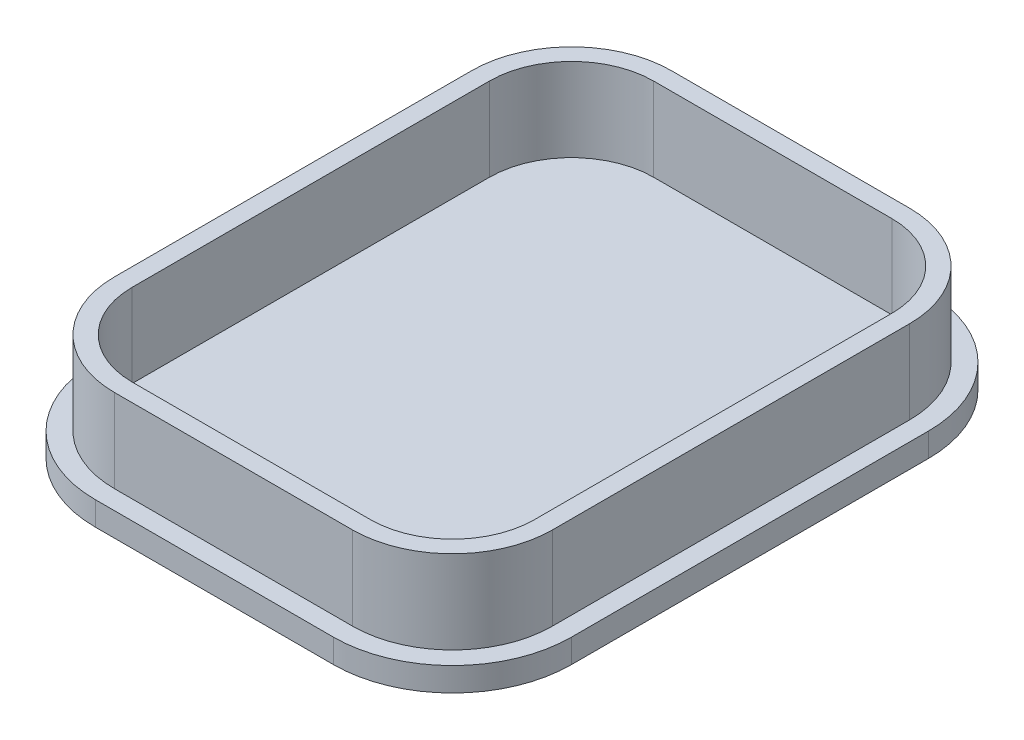
SolidWorks part; units mm, degrees
ref_plane "Plano frontal" through (0, 0, 0) normal (0, 0, 1) x (1, 0, 0)
ref_plane "Plano superior" through (0, 0, 0) normal (0, 1, 0) x (1, 0, 0)
ref_plane "Plano direito" through (0, 0, 0) normal (1, 0, 0) x (0, 0, -1)
sketch "Esboço1" plane through (0, 0, 0) normal (0, 1, 0) x (1, 0, 0)
  line L0 (-10.3488, -24.7614) -> (9.6512, -24.7614)
  line L1 (-20.3488, -14.7614) -> (-20.3488, 15.2386)
  line L2 (-10.3488, 25.2386) -> (9.6512, 25.2386)
  line L3 (19.6512, -14.7614) -> (19.6512, 15.2386)
  line L4 (-20.3488, -24.7614) -> (19.6512, 25.2386) construction
  line L5 (-20.3488, 25.2386) -> (19.6512, -24.7614) construction
  arc A0 (9.6512, 25.2386) -> (19.6512, 15.2386) centre (9.6512, 15.2386) cw
  arc A1 (9.6512, -24.7614) -> (19.6512, -14.7614) centre (9.6512, -14.7614) ccw
  arc A2 (-10.3488, -24.7614) -> (-20.3488, -14.7614) centre (-10.3488, -14.7614) cw
  arc A3 (-20.3488, 15.2386) -> (-10.3488, 25.2386) centre (-10.3488, 15.2386) cw
  point P0 (-0.3488, 0.2386)
  dimension "D1" = 10
extrude "Ressalto-extrusão1" add sketch "Esboço1" along normal blind 2
sketch "Esboço2" plane through (0, 2, 0) normal (0, 1, 0) x (1, 0, 0)
  line L4 (-17.2488, 15.2386) -> (-17.2488, -14.7614)
  line L5 (-10.3488, -21.6614) -> (9.6512, -21.6614)
  line L6 (16.5512, -14.7614) -> (16.5512, 15.2386)
  line L7 (9.6512, 22.1386) -> (-10.3488, 22.1386)
  line L8 (-18.7488, 15.2386) -> (-18.7488, -14.7614)
  line L9 (-10.3488, -23.1614) -> (9.6512, -23.1614)
  line L10 (18.0512, -14.7614) -> (18.0512, 15.2386)
  line L11 (9.6512, 23.6386) -> (-10.3488, 23.6386)
  line L12 (-18.7488, 15.2386) -> (-18.7488, -14.7614)
  line L13 (-10.3488, -23.1614) -> (9.6512, -23.1614)
  line L14 (18.0512, -14.7614) -> (18.0512, 15.2386)
  line L15 (9.6512, 23.6386) -> (-10.3488, 23.6386)
  arc A4 (-17.2488, -14.7614) -> (-10.3488, -21.6614) centre (-10.3488, -14.7614) ccw
  arc A5 (9.6512, -21.6614) -> (16.5512, -14.7614) centre (9.6512, -14.7614) ccw
  arc A6 (16.5512, 15.2386) -> (9.6512, 22.1386) centre (9.6512, 15.2386) ccw
  arc A7 (-10.3488, 22.1386) -> (-17.2488, 15.2386) centre (-10.3488, 15.2386) ccw
  arc A8 (-18.7488, -14.7614) -> (-10.3488, -23.1614) centre (-10.3488, -14.7614) ccw
  arc A9 (9.6512, -23.1614) -> (18.0512, -14.7614) centre (9.6512, -14.7614) ccw
  arc A10 (18.0512, 15.2386) -> (9.6512, 23.6386) centre (9.6512, 15.2386) ccw
  arc A11 (-10.3488, 23.6386) -> (-18.7488, 15.2386) centre (-10.3488, 15.2386) ccw
  arc A12 (-18.7488, -14.7614) -> (-10.3488, -23.1614) centre (-10.3488, -14.7614) ccw
  arc A13 (9.6512, -23.1614) -> (18.0512, -14.7614) centre (9.6512, -14.7614) ccw
  arc A14 (18.0512, 15.2386) -> (9.6512, 23.6386) centre (9.6512, 15.2386) ccw
  arc A15 (-10.3488, 23.6386) -> (-18.7488, 15.2386) centre (-10.3488, 15.2386) ccw
  dimension "D1" = 1.6
  dimension "D2" = 1.5
extrude "Ressalto-extrusão2" add sketch "Esboço2" along normal blind 7
